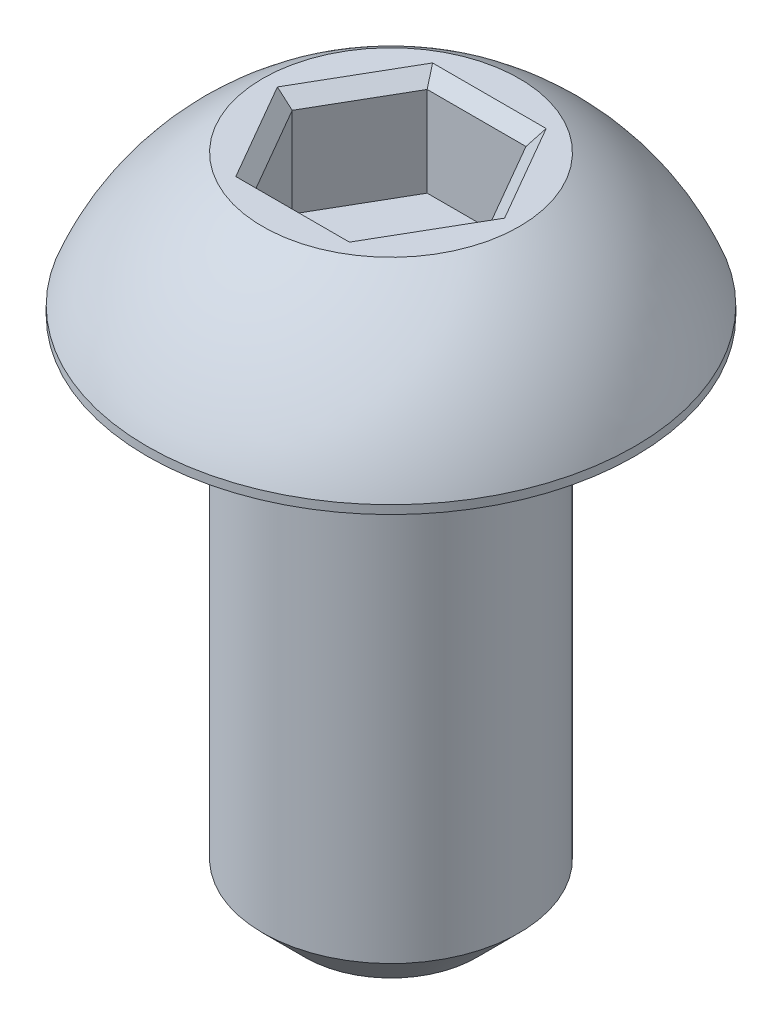
SolidWorks part; units mm, degrees
material "AISI Acier inoxydable type 316L"
ref_plane "Plan de face" through (0, 0, 0) normal (0, 0, 1) x (1, 0, 0)
ref_plane "Plan de dessus" through (0, 0, 0) normal (0, 1, 0) x (1, 0, 0)
ref_plane "Plan de droite" through (0, 0, 0) normal (1, 0, 0) x (0, 0, -1)
sketch "Esquisse1" plane through (0, 0, 0) normal (0, 0, 1) x (1, 0, 0)
  line L0 (0, 6.973) -> (0, -16.342) construction
  line L1 (1.5, -5.5) -> (1, -6)
  line L2 (0, 1.65) -> (1.5, 1.65)
  line L3 (2.85, 0.1) -> (2.85, 0)
  line L4 (2.85, 0) -> (1.5, 0)
  line L5 (1.5, 0) -> (1.5, -5.5)
  line L7 (1, -6) -> (0, -6)
  line L8 (0, -6) -> (0, 1.65)
  arc A0 (1.5, 1.65) -> (2.85, 0.1) centre (0, -1.0194) cw
  point P9 (1.5, -6)
  point P14 (0, 0)
  point P15 (1.5, 1.65)
  dimension "D5" = 0.1
  dimension "D1" = 1.65
  dimension "D2" = 5.7
  dimension "D3" = 3
  dimension "D4" = 6
  dimension "D7" = 3
revolve "Révolution1" add sketch "Esquisse1" angle 360 about L0
cosmetic thread "Représentation de filetage1" parameters "D2"=2.439
sketch "Esquisse2" plane through (0, 1.65, 0) normal (0, 1, 0) x (1, 0, 0)
  line L0 (-1.1547, 0) -> (-0.5774, -1)
  line L1 (1.1547, 0) -> (0.5774, 1)
  line L2 (0.5774, 1) -> (-0.5774, 1)
  line L3 (-0.5774, 1) -> (-1.1547, 0)
  line L4 (-0.5774, -1) -> (0.5774, -1)
  line L5 (0.5774, -1) -> (1.1547, 0)
  circle A0 centre (0, 0) radius 1 construction
  dimension "D1" = 2
extrude "Enlèv. mat.-Extru.1" cut sketch "Esquisse2" against normal blind 1.2
chamfer "Chanfrein1" distance 0.15 angle 45 6 edges at (-0.866, 1.65, -0.5) (-0.866, 1.65, 0.5) (0, 1.65, 1) (0.866, 1.65, 0.5) (0.866, 1.65, -0.5) (0, 1.65, -1)
